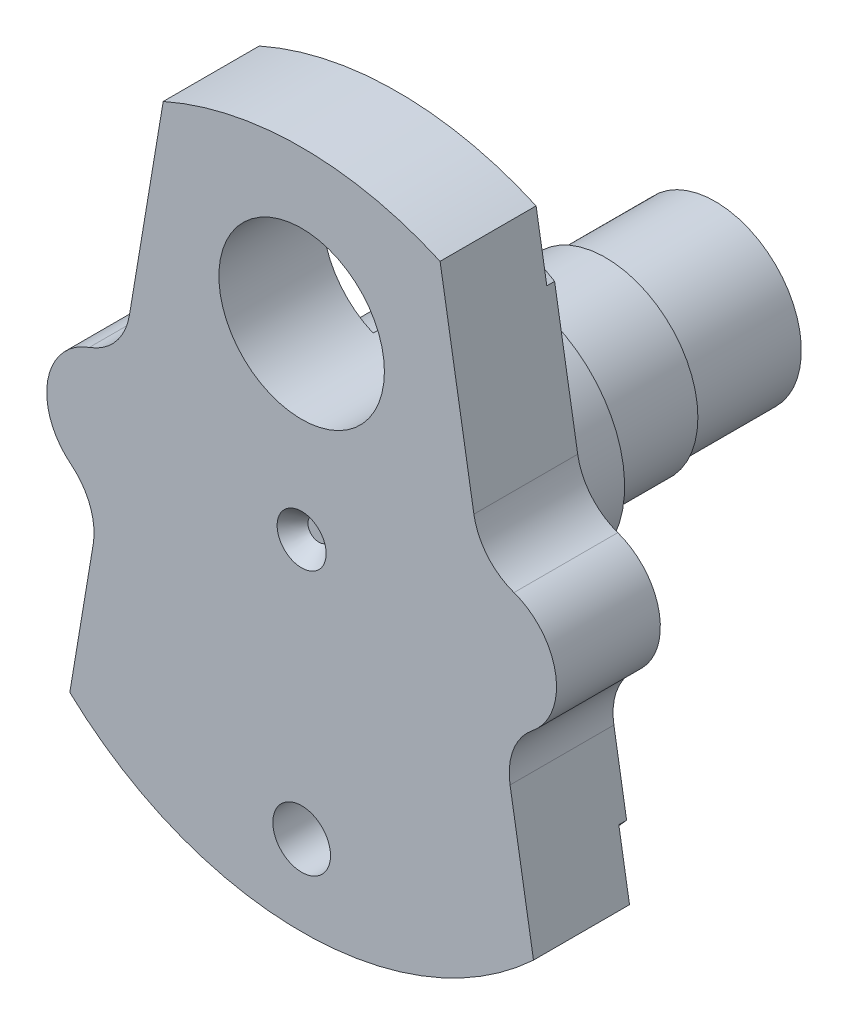
SolidWorks part; units mm, degrees
ref_plane "Front Plane" through (0, 0, 0) normal (0, 0, 1) x (1, 0, 0)
ref_plane "Top Plane" through (0, 0, 0) normal (0, 1, 0) x (1, 0, 0)
ref_plane "Right Plane" through (0, 0, 0) normal (1, 0, 0) x (0, 0, -1)
sketch "Sketch1" plane through (0, 0, 0) normal (0, 0, 1) x (1, 0, 0)
  line L0 (36.1365, -18.7745) -> (40.1958, -43.0492)
  line L1 (24.0031, 53.7846) -> (29.8621, 18.7473)
  line L7 (-24.0031, 53.7846) -> (-29.8621, 18.7473)
  line L10 (-36.1365, -18.7745) -> (-40.1958, -43.0492)
  arc A0 (-40.1958, -43.0492) -> (40.1958, -43.0492) centre (0, 0) ccw
  circle A1 centre (0, 32.4) radius 14.35
  circle A4 centre (0.0044, -44.95) radius 5
  arc A5 (-36.8149, 10.45) -> (-40.0101, -8.6749) centre (-33.1, 0) ccw
  arc A6 (40.0101, -8.6749) -> (36.1365, -18.7745) centre (46.6541, -17.0157) ccw
  arc A7 (-36.8149, 10.45) -> (-29.8621, 18.7473) centre (-40.3904, 20.5078) ccw
  arc A8 (-40.0101, -8.6749) -> (-36.1365, -18.7745) centre (-46.6541, -17.0157) cw
  arc A9 (36.8149, 10.45) -> (40.0101, -8.6749) centre (33.1, 0) cw
  arc A10 (36.8149, 10.45) -> (29.8621, 18.7473) centre (40.3904, 20.5078) cw
  arc A11 (24.0031, 53.7846) -> (-24.0031, 53.7846) centre (0, 0) ccw
extrude "Boss-Extrude1" add sketch "Sketch1" against normal blind 18
sketch "Sketch2" plane through (0, 0, -18) normal (0, 0, -1) x (-1, 0, 0)
  circle A0 centre (0, 0) radius 20
extrude "Boss-Extrude2" add sketch "Sketch2" along normal blind 18
sketch "Sketch3" plane through (0, 0, -36) normal (0, 0, -1) x (-1, 0, 0)
  circle A0 centre (0, 0) radius 16
extrude "Boss-Extrude3" add sketch "Sketch3" along normal blind 35.7
sketch "Sketch5" plane through (0, 0, -71.7) normal (0, 0, -1) x (-1, 0, 0)
  circle A0 centre (0, 0) radius 14.935
extrude "Cut-Extrude1" cut sketch "Sketch5" against normal blind 19 flip side to cut
sketch "Sketch6" plane through (0, 0, 0) normal (0, 0, 1) x (1, 0, 0)
  circle A0 centre (0, 32.4) radius 14.35
sketch "Sketch7" plane through (0, 0, 0) normal (0, 0, 1) x (1, 0, 0)
  circle A0 centre (0, 0) radius 4.25
extrude "Cut-Extrude3" cut sketch "Sketch7" against normal blind 3 draft 38
sketch "Sketch9" plane through (0, 0, -18) normal (0, 0, -1) x (-1, 0, 0)
  circle A0 centre (0, 0) radius 49.9231
extrude "Cut-Extrude4" cut sketch "Sketch9" against normal blind 1.35 flip side to cut
extrude "Cut-Extrude5" cut sketch "Sketch6" against normal blind 21.7
